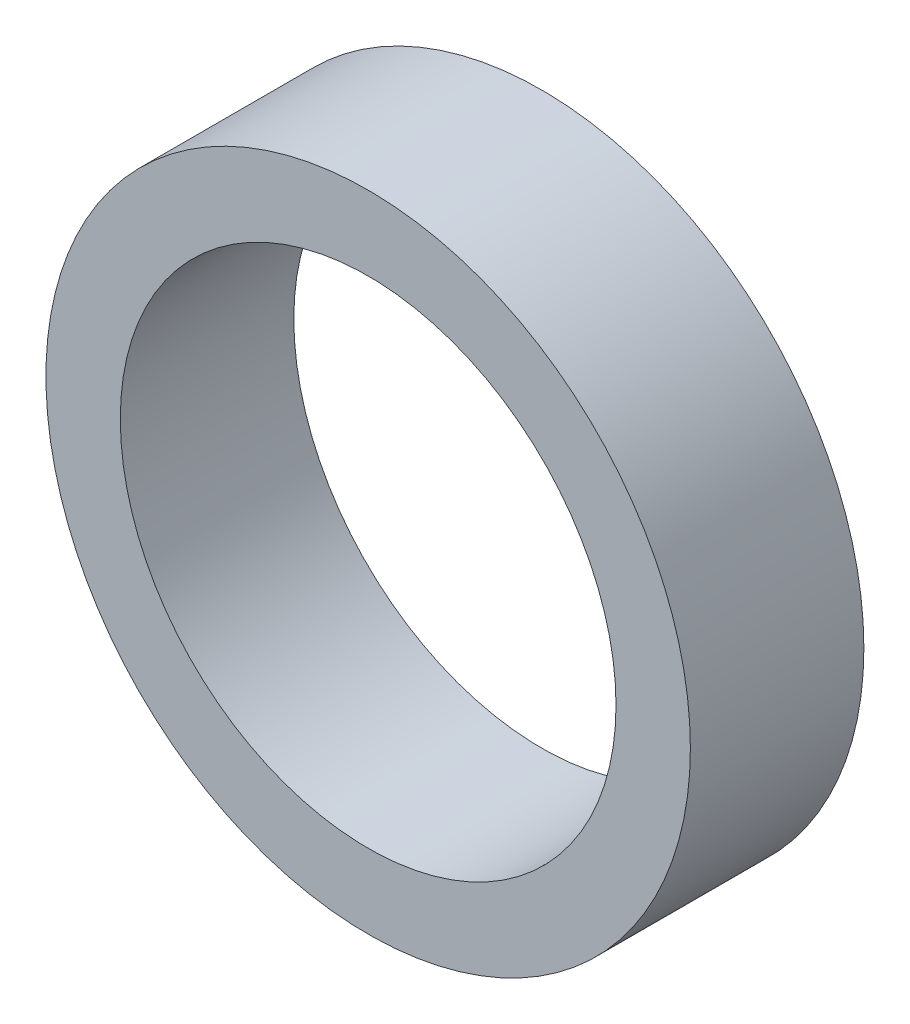
SolidWorks part; units mm, degrees
ref_plane "Front Plane" through (0, 0, 0) normal (0, 0, 1) x (1, 0, 0)
ref_plane "Top Plane" through (0, 0, 0) normal (0, 1, 0) x (1, 0, 0)
ref_plane "Right Plane" through (0, 0, 0) normal (1, 0, 0) x (0, 0, -1)
sketch "Sketch1" plane through (0, 0, 0) normal (0, 0, 1) x (1, 0, 0)
  circle A0 centre (0, 0) radius 10
  circle A1 centre (0, 0) radius 13
extrude "Boss-Extrude1" add sketch "Sketch1" along normal blind 7
